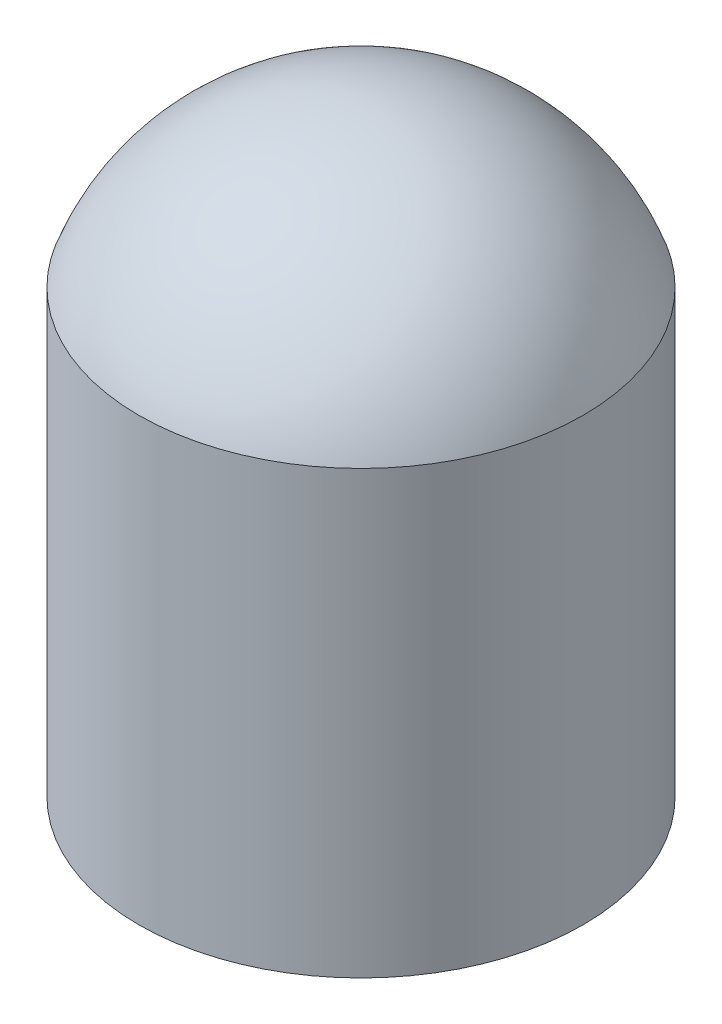
SolidWorks part; units mm, degrees
ref_plane "Front Plane" through (0, 0, 0) normal (0, 0, 1) x (1, 0, 0)
ref_plane "Top Plane" through (0, 0, 0) normal (0, 1, 0) x (1, 0, 0)
ref_plane "Right Plane" through (0, 0, 0) normal (1, 0, 0) x (0, 0, -1)
sketch "Sketch2" plane through (0, 0, 0) normal (0, 0, 1) x (1, 0, 0)
  line L0 (0, 0) -> (0, 8)
  line L1 (2.9871, -2.7221) -> (3.9871, -2.7221)
  line L2 (3.9871, -2.7221) -> (3.9871, 5.2)
  arc A0 (2.9871, -2.7221) -> (0, 0) centre (0, -3) ccw
  arc A2 (3.9871, 5.2) -> (0, 8) centre (0, 3.7613) ccw
  dimension "D2" = 3
  dimension "D1" = 8
  dimension "D3" = 1
  dimension "D4" = 2.8
revolve "Revolve1" add sketch "Sketch2" angle 360 about L0
